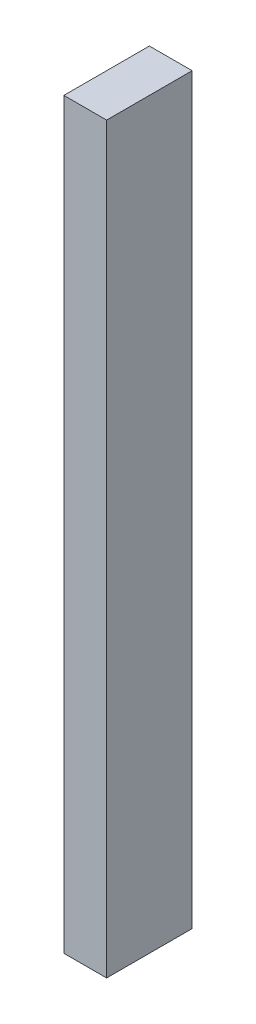
SolidWorks part; units mm, degrees
ref_plane "Front Plane" through (0, 0, 0) normal (0, 0, 1) x (1, 0, 0)
ref_plane "Top Plane" through (0, 0, 0) normal (0, 1, 0) x (1, 0, 0)
ref_plane "Right Plane" through (0, 0, 0) normal (1, 0, 0) x (0, 0, -1)
sketch "Sketch1" plane through (0, 0, 0) normal (0, 1, 0) x (1, 0, 0)
  line L1 (20, -40) -> (-20, -40)
  line L2 (20, -40) -> (20, 40)
  line L3 (20, 40) -> (-20, 40)
  line L4 (-20, -40) -> (-20, 40)
  line L5 (20, -40) -> (-20, 40) construction
  line L6 (20, 40) -> (-20, -40) construction
  point P0 (0, 0)
  dimension "D1" = 80
  dimension "D2" = 40
extrude "Boss-Extrude1" add sketch "Sketch1" along normal blind 695
